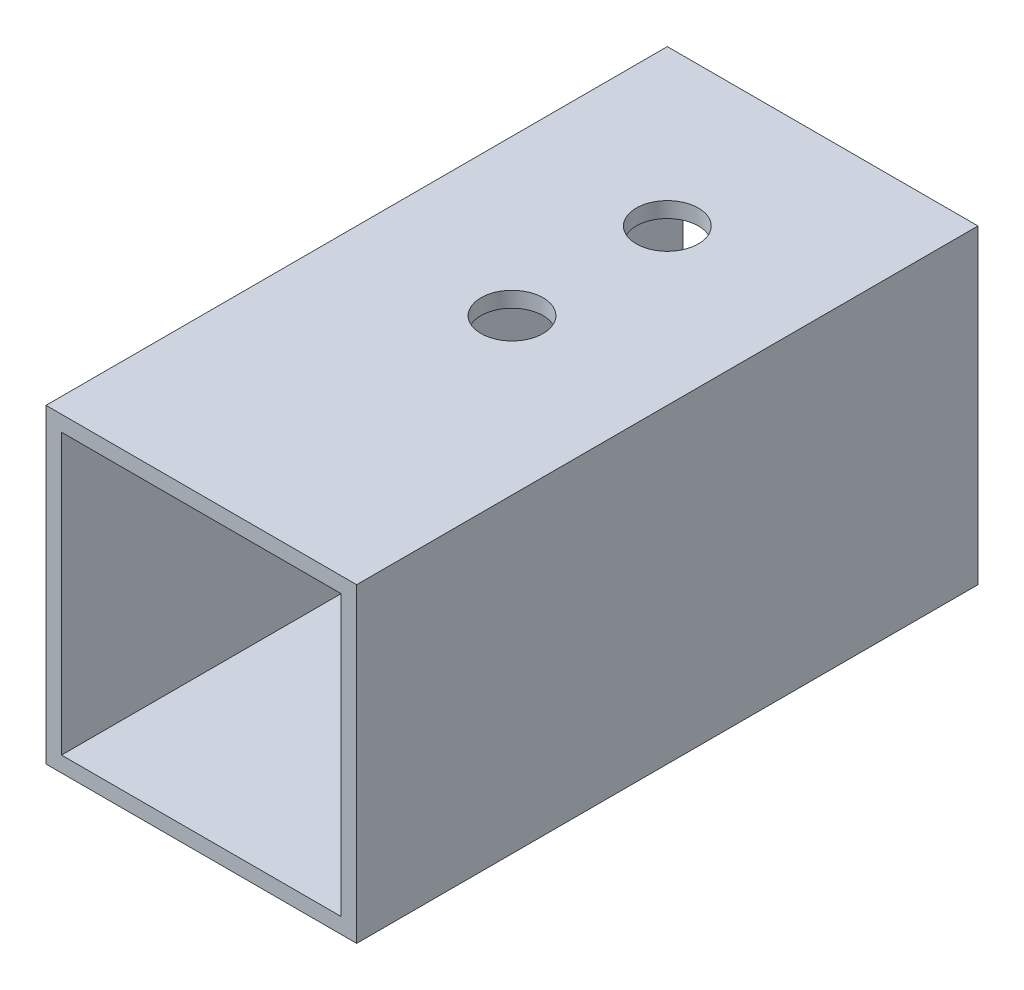
SolidWorks part; units mm, degrees
ref_plane "Front Plane" through (0, 0, 0) normal (0, 0, 1) x (1, 0, 0)
ref_plane "Top Plane" through (0, 0, 0) normal (0, 1, 0) x (1, 0, 0)
ref_plane "Right Plane" through (0, 0, 0) normal (1, 0, 0) x (0, 0, -1)
sketch "Sketch1" plane through (0, 0, 0) normal (0, 0, 1) x (1, 0, 0)
  line L1 (-20, -20) -> (20, -20)
  line L2 (-20, -20) -> (-20, 20)
  line L3 (-20, 20) -> (20, 20)
  line L4 (20, -20) -> (20, 20)
  line L5 (-20, -20) -> (20, 20) construction
  line L6 (-20, 20) -> (20, -20) construction
  line L7 (-18, -18) -> (18, -18)
  line L8 (-18, -18) -> (-18, 18)
  line L9 (-18, 18) -> (18, 18)
  line L10 (18, -18) -> (18, 18)
  line L11 (-18, -18) -> (18, 18) construction
  line L12 (-18, 18) -> (18, -18) construction
  point P0 (0, 0)
  point P6 (0, 0)
  dimension "D1" = 40
  dimension "D2" = 2
extrude "Boss-Extrude1" add sketch "Sketch1" along normal blind 80
sketch "Sketch2" plane through (0, 20, 0) normal (0, 1, 0) x (1, 0, 0)
  line L0 (20, 0) -> (-20, 0) construction
  circle A0 centre (0, -20) radius 4
  circle A1 centre (0, -40) radius 4
  point P4 (0, 0)
  point P7 (0, 0)
  dimension "D3" = 8
  dimension "D1" = 20
  dimension "D2" = 20
extrude "Cut-Extrude1" cut sketch "Sketch2" against normal up to next
sketch "Sketch3" plane through (0, -20, 0) normal (0, -1, 0) x (1, 0, 0)
  line L0 (-20, 0) -> (20, 0) construction
  circle A0 centre (0, 20) radius 4
  point P2 (0, 0)
  dimension "D1" = 8
  dimension "D2" = 20
extrude "Cut-Extrude2" cut sketch "Sketch3" against normal up to next
